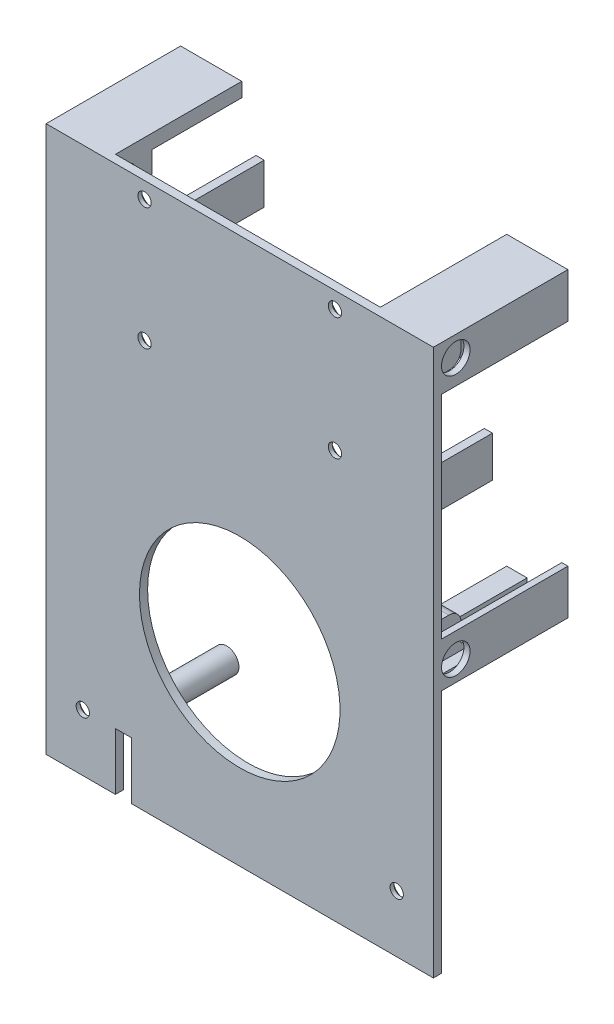
SolidWorks part; units mm, degrees
ref_plane "Front Plane" through (0, 0, 0) normal (0, 0, 1) x (1, 0, 0)
ref_plane "Top Plane" through (0, 0, 0) normal (0, 1, 0) x (1, 0, 0)
ref_plane "Right Plane" through (0, 0, 0) normal (1, 0, 0) x (0, 0, -1)
sketch "Sketch1" plane through (0, 0, 0) normal (0, 0, 1) x (1, 0, 0)
  line L1 (0, 0) -> (95, 0)
  line L2 (0, 0) -> (0, 134)
  line L3 (0, 134) -> (95, 134)
  line L4 (95, 0) -> (95, 134)
  dimension "D1" = 95
  dimension "D2" = 134
extrude "Boss-Extrude1" add sketch "Sketch1" along normal blind 2
sketch "Sketch6" plane through (0, 0, 0) normal (0, 0, -1) x (-1, 0, 0)
  line L0 (-47.5, 0) -> (-47.5, 134) construction
  line L1 (0, 0) -> (-95, 0) construction
  line L2 (-95, 134) -> (0, 134) construction
  line L3 (-86, 14) -> (-9, 14) construction
  line L4 (-70.85, 100) -> (-24.15, 100) construction
  line L6 (-70.85, 130) -> (-24.15, 130) construction
  point P10 (-47.5, 14)
  point P13 (-47.5, 100)
  point P14 (-47.5, 130)
  dimension "D1" = 46.7
  dimension "D2" = 46.7
  dimension "D3" = 77
  dimension "D4" = 14
  dimension "D5" = 100
  dimension "D6" = 30
hole_wizard "CSK for #4 Flat Head Machine Screw (100)2" positions "Sketch7" profile "Sketch8" countersink size "#4" standard "Superior" end condition through all
sketch "Sketch7" plane through (0, 0, 0) normal (0, 0, -1) x (-1, 0, 0)
  point P0 (-70.85, 130)
  point P3 (-24.15, 130)
  point P6 (-24.15, 100)
  point P9 (-70.85, 100)
  point P12 (-86, 14)
  point P15 (-9, 14)
sketch "Sketch8" plane through (70.85, 130, 0) normal (1, 0, 0) x (0, 1, 0)
  line L0 (0, 0) -> (0, 2)
  line L1 (0, 2) -> (1.632, 2)
  line L2 (1.632, 2) -> (1.6319, 1.0284)
  line L3 (1.6319, 1.0284) -> (2.8575, 0)
  line L5 (2.8575, 0) -> (0, 0)
  line L6 (-1.6319, 1.0284) -> (-2.8575, 0) construction
  line L11 (0, -6.35) -> (0, 107.95) construction
  dimension "Thru Hole Dia." = 3.2639
  dimension "Thru Hole Depth" = 2
  dimension "Near C'Sink Dia." = 5.715
  dimension "Near C'Sink Angle" = 100
sketch "Sketch12" plane through (0, 0, 2) normal (0, 0, 1) x (1, 0, 0)
  line L0 (47.5, 0) -> (47.5, 134) construction
  line L1 (0, 0) -> (95, 0) construction
  circle A0 centre (47.5, 52.5) radius 35
  dimension "D2" = 70
  dimension "D1" = 52.5
sketch "Sketch13" plane through (0, 0, 0) normal (0, 0, -1) x (-1, 0, 0)
  line L0 (-47.5, 0) -> (-47.5, 134) construction
  line L1 (0, 0) -> (-95, 0) construction
  circle A0 centre (-47.5, 45.5) radius 24.6
  dimension "D1" = 49.2
  dimension "D2" = 45.5
extrude "Cut-Extrude2" cut sketch "Sketch13" against normal through all
sketch "Sketch14" plane through (0, 0, 0) normal (0, 0, -1) x (-1, 0, 0)
  line L0 (-72, 70.1) -> (-23, 70.1) construction
  line L1 (-23, 20.9) -> (-72, 20.9) construction
  line L2 (-47.5, 0) -> (-47.5, 134) construction
  circle A1 centre (-47.5, 45.5) radius 24.6 construction
  circle A2 centre (-72, 70.1) radius 3
  circle A3 centre (-23, 70.1) radius 3
  circle A4 centre (-72, 20.9) radius 3
  circle A5 centre (-23, 20.9) radius 3
  point P4 (-47.5, 20.9)
  point P9 (-47.5, 70.1)
  dimension "D3" = 6
  dimension "D1" = 49
  dimension "D2" = 49
extrude "Boss-Extrude4" add sketch "Sketch14" along normal blind 19.3
sketch "Sketch15" plane through (0, 0, -19.3) normal (0, 0, -1) x (-1, 0, 0)
  circle A0 centre (-72, 70.1) radius 1.15
  circle A1 centre (-23, 70.1) radius 1.15
  circle A2 centre (-23, 20.9) radius 1.15
  circle A3 centre (-72, 20.9) radius 1.15
  dimension "D1" = 2.3
extrude "Cut-Extrude3" cut sketch "Sketch15" against normal blind 15
sketch "Sketch16" plane through (0, 0, 0) normal (0, 0, -1) x (-1, 0, 0)
  line L0 (0, 0) -> (-95, 0) construction
  line L1 (-17, 0) -> (-21, 0)
  line L2 (-17, 0) -> (-17, 14)
  line L3 (-17, 14) -> (-21, 14)
  line L4 (-21, 0) -> (-21, 14)
  line L5 (-47.5, 0) -> (-47.5, 134) construction
  dimension "D1" = 30.5
  dimension "D2" = 4
  dimension "D3" = 14
extrude "Cut-Extrude4" cut sketch "Sketch16" against normal through all
sketch "Sketch17" plane through (0, 0, 0) normal (0, 0, -1) x (-1, 0, 0)
  line L0 (-95, 0) -> (-95, 134) construction
  line L1 (-95, 134) -> (-80, 134)
  line L2 (-95, 134) -> (-95, 123)
  line L3 (-95, 123) -> (-80, 123)
  line L4 (-80, 134) -> (-80, 123)
  line L5 (-95, 60) -> (-80, 60)
  line L6 (-95, 60) -> (-95, 71)
  line L7 (-95, 71) -> (-80, 71)
  line L8 (-80, 60) -> (-80, 71)
  line L9 (-47.5, 134) -> (-47.5, 0) construction
  line L10 (-15, 60) -> (-15, 71)
  line L11 (0, 71) -> (-15, 71)
  line L12 (0, 60) -> (0, 71)
  line L13 (0, 60) -> (-15, 60)
  line L14 (-15, 134) -> (-15, 123)
  line L15 (0, 123) -> (-15, 123)
  line L16 (0, 134) -> (0, 123)
  line L17 (0, 134) -> (-15, 134)
  dimension "D1" = 15
  dimension "D2" = 11
  dimension "D3" = 11
  dimension "D4" = 15
  dimension "D5" = 74
extrude "Boss-Extrude5" add sketch "Sketch17" along normal blind 31
sketch "Sketch18" plane through (0, 0, -31) normal (0, 0, -1) x (-1, 0, 0)
  line L0 (-80, 134) -> (-95, 134) construction
  line L1 (-93.5, 132) -> (-90.8, 132)
  line L2 (-93.5, 132) -> (-93.5, 62)
  line L3 (-93.5, 62) -> (-90.8, 62)
  line L4 (-90.8, 132) -> (-90.8, 62)
  line L5 (-95, 134) -> (-95, 123) construction
  line L7 (0, 123) -> (0, 134) construction
  line L8 (-4.2, 132) -> (-1.5, 132)
  line L9 (-4.2, 132) -> (-4.2, 62)
  line L10 (-4.2, 62) -> (-1.5, 62)
  line L11 (-1.5, 132) -> (-1.5, 62)
  line L12 (0, 134) -> (-15, 134) construction
  dimension "D1" = 70
  dimension "D2" = 2
  dimension "D3" = 2.7
  dimension "D4" = 1.5
  dimension "D5" = 70
  dimension "D6" = 1.5
  dimension "D7" = 2.7
  dimension "D8" = 2
extrude "Cut-Extrude5" cut sketch "Sketch18" against normal blind 31
sketch "Sketch19" plane through (0, 0, -31) normal (0, 0, -1) x (-1, 0, 0)
  line L0 (-90.8, 123) -> (-90.8, 132) construction
  line L1 (-90.8, 130.5) -> (-76.5, 130.5)
  line L2 (-90.8, 130.5) -> (-90.8, 63.5)
  line L3 (-90.8, 63.5) -> (-76.5, 63.5)
  line L4 (-76.5, 130.5) -> (-76.5, 63.5)
  line L5 (-93.5, 132) -> (-93.5, 123) construction
  line L6 (-90.8, 132) -> (-93.5, 132) construction
  line L7 (-93.5, 62) -> (-90.8, 62) construction
  line L8 (-4.2, 132) -> (-4.2, 123) construction
  line L9 (-4.2, 130.5) -> (-18.5, 130.5)
  line L10 (-4.2, 130.5) -> (-4.2, 63.5)
  line L11 (-4.2, 63.5) -> (-18.5, 63.5)
  line L12 (-18.5, 130.5) -> (-18.5, 63.5)
  line L13 (-1.5, 132) -> (-4.2, 132) construction
  line L14 (-4.2, 62) -> (-1.5, 62) construction
  line L15 (-1.5, 123) -> (-1.5, 132) construction
  point P8 (-93.5, 127.5)
  dimension "D1" = 17
  dimension "D2" = 1.5
  dimension "D3" = 1.5
  dimension "D4" = 17
  dimension "D5" = 1.5
  dimension "D6" = 1.5
extrude "Cut-Extrude6" cut sketch "Sketch19" against normal blind 22
fillet "Fillet5" radius 3 1 edges at (85.4, 123, -9)
fillet "Fillet6" radius 3 1 edges at (9.6, 123, -9)
fillet "Fillet7" radius 3 1 edges at (9.6, 71, -9)
fillet "Fillet8" radius 3 1 edges at (85.4, 71, -9)
sketch "Sketch20" plane through (0, 0, 0) normal (0, 0, -1) x (-1, 0, 0)
  line L0 (-93.5, 132) -> (-93.5, 123) construction
  line L1 (-76.5, 120) -> (-74.5, 120)
  line L2 (-76.5, 120) -> (-76.5, 110)
  line L3 (-76.5, 110) -> (-74.5, 110)
  line L4 (-74.5, 120) -> (-74.5, 110)
  line L13 (-76.5, 90) -> (-74.5, 90)
  line L14 (-76.5, 90) -> (-76.5, 80)
  line L15 (-76.5, 80) -> (-74.5, 80)
  line L16 (-74.5, 90) -> (-74.5, 80)
  line L17 (-93.5, 62) -> (-93.5, 71) construction
  line L18 (-70.85, 100) -> (-24.15, 100) construction
  line L19 (-47.5, 134) -> (-47.5, 0) construction
  line L20 (-80, 134) -> (-15, 134) construction
  line L21 (-20.5, 90) -> (-20.5, 80)
  line L22 (-18.5, 80) -> (-20.5, 80)
  line L23 (-18.5, 90) -> (-18.5, 80)
  line L24 (-18.5, 90) -> (-20.5, 90)
  line L25 (-20.5, 120) -> (-20.5, 110)
  line L26 (-18.5, 110) -> (-20.5, 110)
  line L27 (-18.5, 120) -> (-18.5, 110)
  line L28 (-18.5, 120) -> (-20.5, 120)
  dimension "D1" = 17
  dimension "D2" = 17
  dimension "D3" = 2
  dimension "D4" = 2
  dimension "D5" = 10
  dimension "D6" = 10
  dimension "D7" = 10
  dimension "D8" = 10
extrude "Boss-Extrude6" add sketch "Sketch20" along normal blind 31
sketch "Sketch22" plane through (90.8, 0, 0) normal (1, 0, 0) x (0, 0, -1)
  line L2 (0, 123) -> (0, 132) construction
  line L3 (0, 132) -> (31, 132) construction
  line L4 (0, 62) -> (0, 71) construction
  line L6 (0, 62) -> (31, 62) construction
  circle A0 centre (3.5, 129) radius 1.15
  circle A1 centre (3.5, 65) radius 1.15
  dimension "D1" = 2.3
  dimension "D2" = 3
  dimension "D4" = 2.3
  dimension "D5" = 3.5
  dimension "D6" = 3
  dimension "D3" = 3.5
extrude "Cut-Extrude7" cut sketch "Sketch22" against normal through all both and the other way through all
sketch "Sketch23" plane through (95, 0, 0) normal (1, 0, 0) x (0, 0, -1)
  circle A0 centre (3.5, 129) radius 3.5
  circle A1 centre (3.5, 65) radius 3.5
  dimension "D1" = 7
  dimension "D2" = 7
extrude "Cut-Extrude8" cut sketch "Sketch23" against normal blind 1.5
sketch "Sketch24" plane through (0, 0, 0) normal (-1, 0, 0) x (0, 0, 1)
  circle A0 centre (-3.5, 129) radius 3.5
  circle A1 centre (-3.5, 65) radius 3.5
  dimension "D1" = 7
  dimension "D2" = 7
extrude "Cut-Extrude9" cut sketch "Sketch24" against normal blind 1.5
sketch "Sketch25" plane through (0, 0, -31) normal (0, 0, -1) x (-1, 0, 0)
  line L0 (-15, 60) -> (0, 60) construction
  line L1 (-7, 60) -> (-10, 60)
  line L2 (-7, 60) -> (-7, 63.5)
  line L3 (-7, 63.5) -> (-10, 63.5)
  line L4 (-10, 60) -> (-10, 63.5)
  line L6 (-95, 60) -> (-80, 60) construction
  line L7 (-88, 60) -> (-85, 60)
  line L8 (-88, 60) -> (-88, 63.5)
  line L9 (-88, 63.5) -> (-85, 63.5)
  line L10 (-85, 60) -> (-85, 63.5)
  line L11 (-90.8, 63.5) -> (-80, 63.5) construction
  line L12 (-15, 63.5) -> (-15, 60) construction
  line L13 (-80, 60) -> (-80, 71) construction
  line L14 (-95, 71) -> (-95, 60) construction
  line L15 (0, 60) -> (0, 71) construction
  line L16 (-15, 63.5) -> (-4.2, 63.5) construction
  point P16 (0, 0)
  dimension "D1" = 5
  dimension "D2" = 5
  dimension "D3" = 7
  dimension "D4" = 7
extrude "Cut-Extrude10" cut sketch "Sketch25" against normal blind 17
